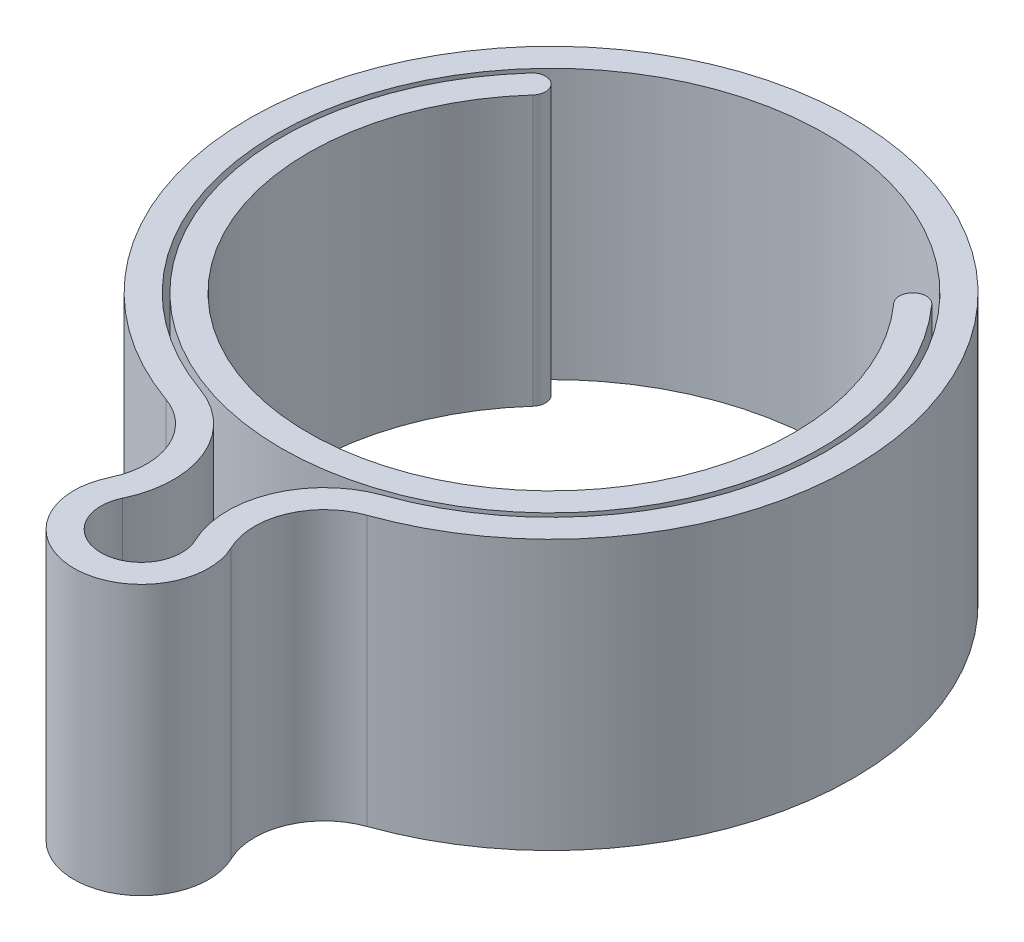
SolidWorks part; units mm, degrees
ref_plane "Спереди" through (0, 0, 0) normal (0, 0, 1) x (1, 0, 0)
ref_plane "Сверху" through (0, 0, 0) normal (0, 1, 0) x (1, 0, 0)
ref_plane "Справа" through (0, 0, 0) normal (1, 0, 0) x (0, 0, -1)
sketch "Эскиз1" plane through (0, 0, 0) normal (0, 1, 0) x (1, 0, 0)
  arc A0 (-3.345, 3.0101) -> (3.345, 3.0101) centre (0, 0) ccw
  arc A1 (-3.7167, 3.3446) -> (3.7167, 3.3446) centre (0, 0) ccw
  arc A2 (1.6966, -4.8095) -> (-1.6966, -4.8095) centre (0, 0) ccw
  arc A3 (1.8629, -5.2811) -> (-1.8629, -5.2811) centre (0, 0) ccw
  arc A4 (-1.1271, -7.0595) -> (1.1271, -7.0595) centre (0, -7.6) ccw
  arc A12 (1.8629, -5.2811) -> (1.1271, -7.0595) centre (2.293, -6.5004) ccw
  arc A13 (-1.1271, -7.0595) -> (-1.8629, -5.2811) centre (-2.293, -6.5004) ccw
  arc A14 (-0.6763, -7.2757) -> (0.6763, -7.2757) centre (0, -7.6) ccw
  arc A15 (1.6966, -4.8095) -> (0.6763, -7.2757) centre (2.293, -6.5004) ccw
  arc A16 (-0.6763, -7.2757) -> (-1.6966, -4.8095) centre (-2.293, -6.5004) ccw
  arc A17 (-3.345, 3.0101) -> (-3.7167, 3.3446) centre (-3.5309, 3.1773) ccw
  arc A18 (3.7167, 3.3446) -> (3.345, 3.0101) centre (3.5309, 3.1773) ccw
extrude "Бобышка-Вытянуть1" add sketch "Эскиз1" along normal blind 5 contours A1 A18 A0 A17 | A13 A4 A12 A3 A14 A16 A2 A15
